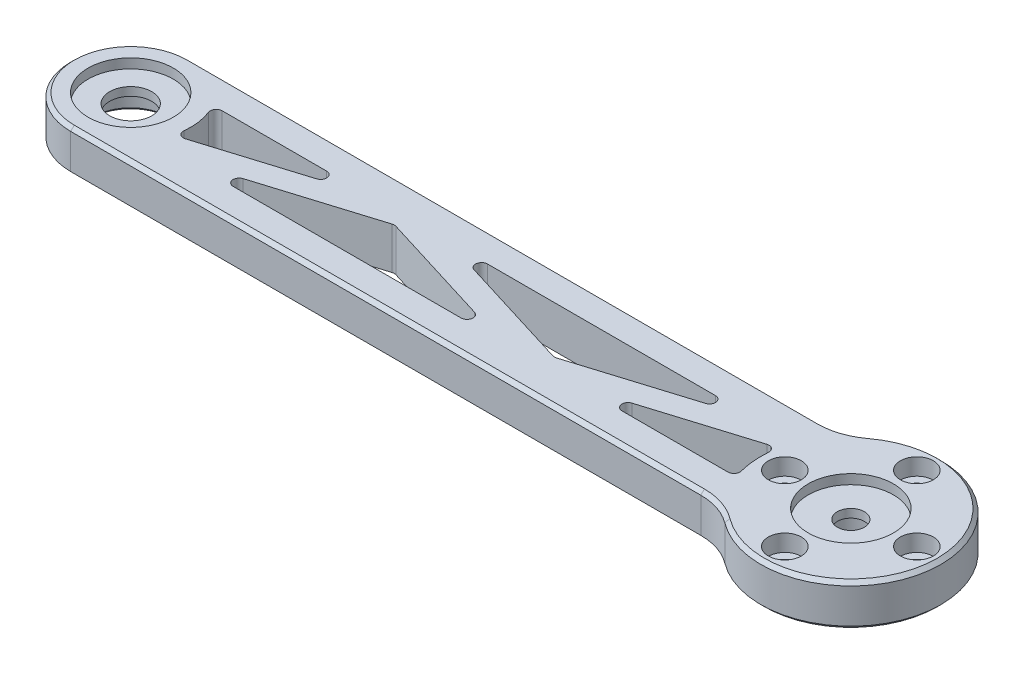
SolidWorks part; units mm, degrees
material "三聚氰胺甲醛树脂"
ref_plane "前视基准面" through (0, 0, 0) normal (0, 0, 1) x (1, 0, 0)
ref_plane "上视基准面" through (0, 0, 0) normal (0, 1, 0) x (1, 0, 0)
ref_plane "右视基准面" through (0, 0, 0) normal (1, 0, 0) x (0, 0, -1)
sketch "草图1" plane through (0, 0, 0) normal (0, 1, 0) x (1, 0, 0)
  line L0 (-120, 10) -> (-11.1803, 10)
  line L1 (-120, -10) -> (-11.1803, -10)
  line L2 (-104.5583, -5) -> (-53.3228, -5)
  line L3 (-111.3397, 5) -> (-85.722, 5)
  line L4 (-111.3397, -5) -> (-78.9405, 5) construction
  line L5 (-78.9405, 5) -> (-46.5413, -5) construction
  line L6 (-46.5413, -5) -> (-14.1421, 5) construction
  line L7 (-110.3438, -2.5995) -> (-85.722, 5)
  line L8 (-104.5583, -5) -> (-78.9405, 2.9069)
  line L9 (-78.9405, 2.9069) -> (-53.3228, -5)
  line L10 (-72.1591, 5) -> (-46.5413, -2.9069)
  line L11 (-46.5413, -2.9069) -> (-20.9236, 5)
  line L12 (-39.7599, -5) -> (-14.7515, 2.7188)
  line L13 (-72.1591, 5) -> (-20.9236, 5)
  line L14 (-39.7599, -5) -> (-14.1421, -5)
  circle A0 centre (0, 0) radius 11 construction
  circle A1 centre (-11, 0) radius 1.35
  circle A2 centre (0, 11) radius 1.35
  circle A3 centre (11, 0) radius 1.35
  circle A4 centre (0, -11) radius 1.35
  arc A7 (-14.7515, 2.7188) -> (-14.1421, -5) centre (0, 0) ccw
  arc A9 (-120, 10) -> (-120, -10) centre (-120, 0) ccw
  arc A10 (-11.1803, -10) -> (-11.1803, 10) centre (0, 0) ccw
  circle A11 centre (0, 0) radius 15 construction
  arc A12 (-110.3438, -2.5995) -> (-111.3397, 5) centre (-120, 0) ccw
  circle A13 centre (-120, 0) radius 10 construction
  point P14 (0, 0)
  dimension "D1" = 22
  dimension "D2" = 2.7
  dimension "D5" = 30
  dimension "D7" = 20
  dimension "D8" = 120
  dimension "D9" = 5
  dimension "D10" = 5
  dimension "D11" = 2
  dimension "D12" = 2
  dimension "D13" = 2
  dimension "D14" = 2
  dimension "D15" = 2
  dimension "D16" = 2
extrude "凸台-拉伸1" add sketch "草图1" along normal blind 7
fillet "圆角1" radius 1 3 edges at (-85.722, 3.5, -5) (-110.3438, 3.5, 2.5995) (-111.3397, 3.5, -5)
fillet "圆角2" radius 1 3 edges at (-53.3228, 3.5, 5) (-78.9405, 3.5, -2.9069) (-104.5583, 3.5, 5)
fillet "圆角3" radius 1 3 edges at (-20.9236, 3.5, -5) (-46.5413, 3.5, 2.9069) (-72.1591, 3.5, -5)
fillet "圆角4" radius 1 3 edges at (-39.7599, 3.5, 5) (-14.1421, 3.5, 5) (-14.7515, 3.5, -2.7188)
fillet "圆角5" radius 10 2 edges at (-11.1803, 3.5, 10) (-11.1803, 3.5, -10)
ref_plane "基准面1" through (0, 1.2, 0) normal (0, -1, 0) x (-1, 0, 0)
sketch "草图2" plane through (0, 0, 0) normal (0, -1, 0) x (-1, 0, 0)
  circle A0 centre (0, 0) radius 4
  dimension "D1" = 8
extrude "切除-拉伸1" cut sketch "草图2" against normal blind 4
sketch "草图3" plane through (0, 0, 0) normal (0, -1, 0) x (-1, 0, 0)
  circle A0 centre (120, 0) radius 6.1
  dimension "D1" = 12.2
extrude "切除-拉伸2" cut sketch "草图3" against normal blind 4
sketch "草图4" plane through (0, 7, 0) normal (0, 1, 0) x (1, 0, 0)
  circle A0 centre (0, 0) radius 7.1
  dimension "D1" = 14.2
extrude "切除-拉伸4" cut sketch "草图4" against normal blind 1.6 contours A0
sketch "草图5" plane through (0, 7, 0) normal (0, 1, 0) x (1, 0, 0)
  circle A0 centre (-120, 0) radius 7.1
  dimension "D1" = 14.2
extrude "切除-拉伸5" cut sketch "草图5" against normal blind 1.6
sketch "草图6" plane through (0, 5.4, 0) normal (0, 1, 0) x (1, 0, 0)
  circle A0 centre (0, 0) radius 2.25
  circle A1 centre (-120, 0) radius 3.5
  dimension "D1" = 4.5
  dimension "D2" = 7
extrude "切除-拉伸6" cut sketch "草图6" against normal mid plane 10
chamfer "倒角1" distance 0.6 angle 45 12 edges at (-130, 0, 0) (-67.5, 0, 10) (-67.5, 0, -10) (-11.8377, 0, 10.5132) (-11.8377, 0, -10.5132) (15, 0, 0) (-130, 7, 0) (-67.5, 7, 10) (-67.5, 7, -10) (-11.8377, 7, 10.5132) (-11.8377, 7, -10.5132) (15, 7, 0)
chamfer "倒角2" distance 0.5 angle 45 1 edges at (-120, 0, -6.1)
sketch "草图7" plane through (0, 7, 0) normal (0, 1, 0) x (1, 0, 0)
  circle A0 centre (0, 11) radius 2.75
  circle A1 centre (11, 0) radius 2.75
  circle A2 centre (0, -11) radius 2.75
  circle A3 centre (-11, 0) radius 2.75
  point P12 (0, 0)
  dimension "D1" = 5.5
  dimension "D2" = 4
extrude "切除-拉伸7" cut sketch "草图7" against normal blind 2.8
